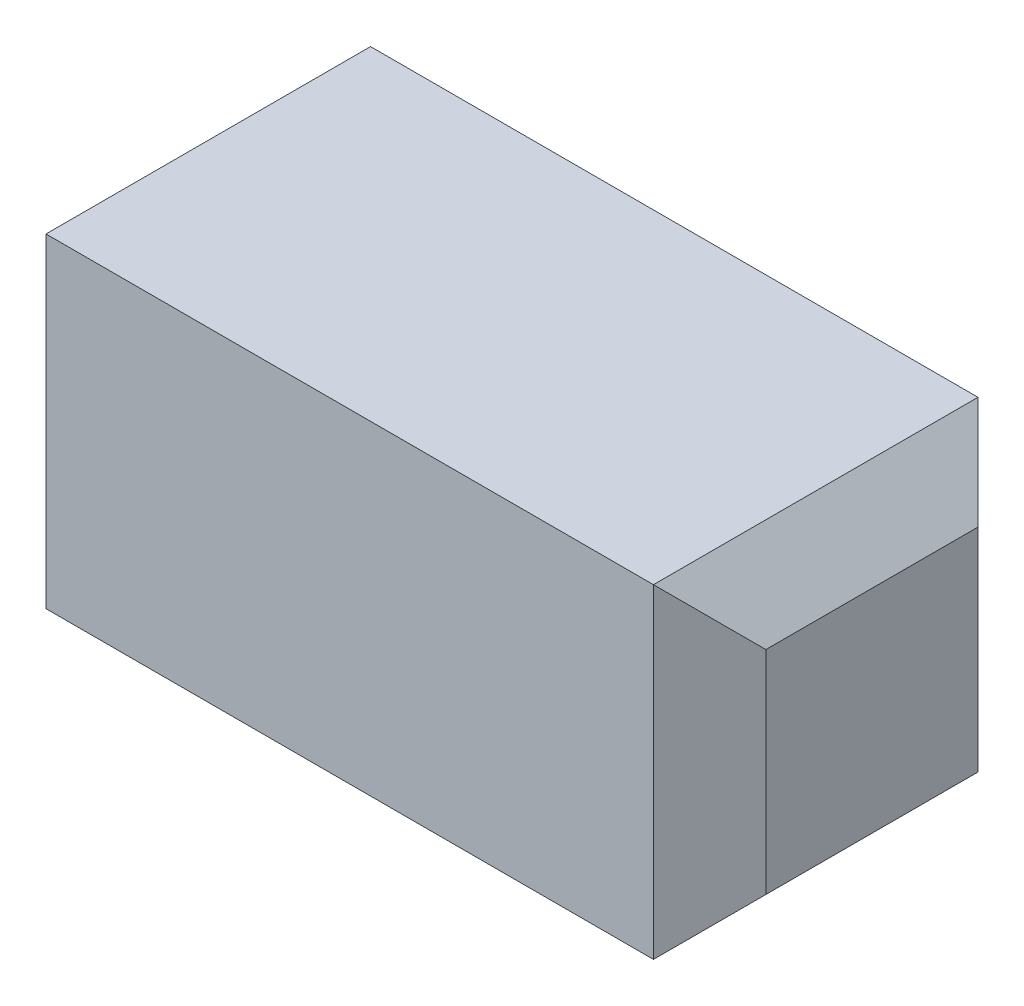
SolidWorks part; units mm, degrees
ref_plane "Front Plane" through (0, 0, 0) normal (0, 0, 1) x (1, 0, 0)
ref_plane "Top Plane" through (0, 0, 0) normal (0, 1, 0) x (1, 0, 0)
ref_plane "Right Plane" through (0, 0, 0) normal (1, 0, 0) x (0, 0, -1)
sketch "Sketch1" plane through (0, 0, 0) normal (1, 0, 0) x (0, 0, -1)
  line L1 (0, 0) -> (4.4003, 0)
  line L2 (0, 0) -> (0, 4.4003)
  line L3 (0, 4.4003) -> (4.4003, 4.4003)
  line L4 (4.4003, 0) -> (4.4003, 4.4003)
  dimension "D1" = 6.223
extrude "Boss-Extrude1" add sketch "Sketch1" along normal blind 9.76
chamfer "Chamfer1" distance 0.762 angle 45 8 edges at (0, 0, -2.2002) (0, 2.2002, -4.4003) (0, 4.4003, -2.2002) (0, 2.2002, 0) (9.76, 4.4003, -2.2002) (9.76, 2.2002, -4.4003) (9.76, 0, -2.2002) (9.76, 2.2002, 0)
